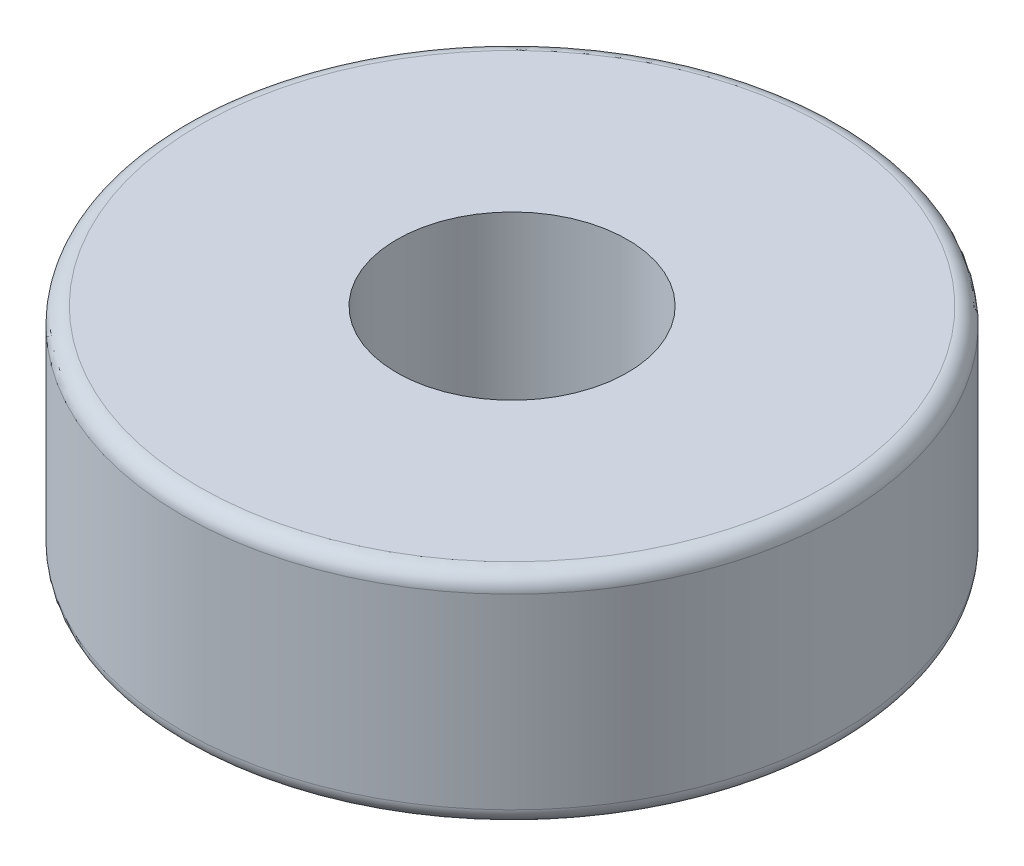
SolidWorks part; units mm, degrees
ref_plane "Front Plane" through (0, 0, 0) normal (0, 0, 1) x (1, 0, 0)
ref_plane "Top Plane" through (0, 0, 0) normal (0, 1, 0) x (1, 0, 0)
ref_plane "Right Plane" through (0, 0, 0) normal (1, 0, 0) x (0, 0, -1)
sketch "Sketch1" plane through (0, 0, 0) normal (0, 1, 0) x (1, 0, 0)
  circle A0 centre (0, 0) radius 10.5
  circle A1 centre (0, 0) radius 30
  dimension "D1" = 21
  dimension "D2" = 60
extrude "Boss-Extrude1" add sketch "Sketch1" along normal blind 20
fillet "Fillet1" radius 1.5 2 edges at (0, 0, 30) (0, 20, 30)
